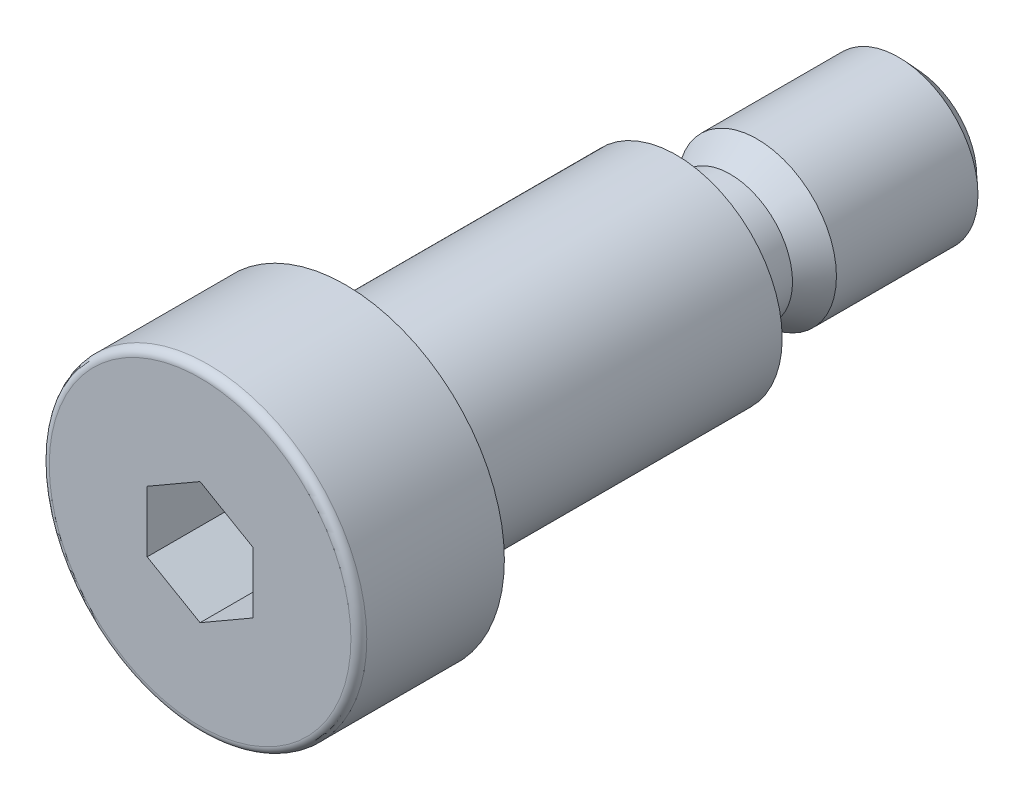
SolidWorks part; units mm, degrees
material "1.0545 (S355N)"
ref_plane "Płaszczyzna przednia" through (0, 0, 0) normal (0, 0, 1) x (1, 0, 0)
ref_plane "Płaszczyzna górna" through (0, 0, 0) normal (0, 1, 0) x (1, 0, 0)
ref_plane "Płaszczyzna prawa" through (0, 0, 0) normal (1, 0, 0) x (0, 0, -1)
sketch "Szkic1" plane through (0, 0, 0) normal (0, 1, 0) x (1, 0, 0)
  line L0 (6, 18.6) -> (4.7, 16.58)
  line L1 (12, -23.5) -> (-12, -23.5)
  line L2 (12, -23.5) -> (12, -12.5)
  line L3 (12, -12.5) -> (-12, -12.5)
  line L4 (-12, -23.5) -> (-12, -12.5)
  line L5 (8, -12.5) -> (-8, -12.5)
  line L6 (8, -12.5) -> (8, 12.5)
  line L7 (8, 12.5) -> (-8, 12.5)
  line L8 (-8, -12.5) -> (-8, 12.5)
  line L9 (-4.7, 12.5) -> (4.7, 12.5)
  line L10 (-4.7, 12.5) -> (-4.7, 16.58)
  line L11 (-4.7, 16.58) -> (4.7, 16.58)
  line L12 (4.7, 12.5) -> (4.7, 16.58)
  line L13 (6, 18.6) -> (6, 29.3)
  line L14 (6, 29.3) -> (4.7, 30.5)
  line L15 (4.7, 30.5) -> (-4.7, 30.5)
  line L16 (-4.7, 30.5) -> (-6, 29.3)
  line L17 (-6, 29.3) -> (-6, 18.6)
  line L18 (-6, 18.6) -> (-4.7, 16.58)
  line L19 (6, 18.6) -> (-6, 18.6) construction
  line L20 (6, 29.3) -> (-6, 29.3) construction
  line L21 (0, -19.9356) -> (0, 25.6583) construction
  line L22 (0, -23.5) -> (0, 30.5)
  point P4 (0, -12.5)
  point P14 (0, -12.5)
  point P15 (0, 12.5)
  point P16 (0, 12.5)
  point P17 (-8, 0)
  point P23 (0, 18.6)
  point P25 (0, 30.5)
  point P26 (0, 16.58)
  point P27 (0, 29.3)
  dimension "D1" = 24
  dimension "D2" = 11
  dimension "D3" = 16
  dimension "l1" = 25
  dimension "D5" = 9.4
  dimension "D6" = 18
  dimension "D7" = 12
  dimension "D8" = 9.4
  dimension "D9" = 1.2
  dimension "D10" = 2.02
  dimension "D11" = 10.7
revolve "Obrót1" add sketch "Szkic1" angle 360 about L22
sketch "Szkic2" plane through (0, 0, 23.5) normal (0, 0, 1) x (1, 0, 0)
  line L1 (4, 2.3094) -> (0, 4.6188)
  line L2 (0, 4.6188) -> (-4, 2.3094)
  line L3 (-4, 2.3094) -> (-4, -2.3094)
  line L4 (-4, -2.3094) -> (0, -4.6188)
  line L5 (0, -4.6188) -> (4, -2.3094)
  line L6 (4, -2.3094) -> (4, 2.3094)
  circle A0 centre (0, 0) radius 4 construction
  dimension "D1" = 8
extrude "Wytnij-wyciągnięcie1" cut sketch "Szkic2" against normal blind 6.6
fillet "Zaokrąglenie1" radius 0.6 1 edges at (12, 0, 23.5)
